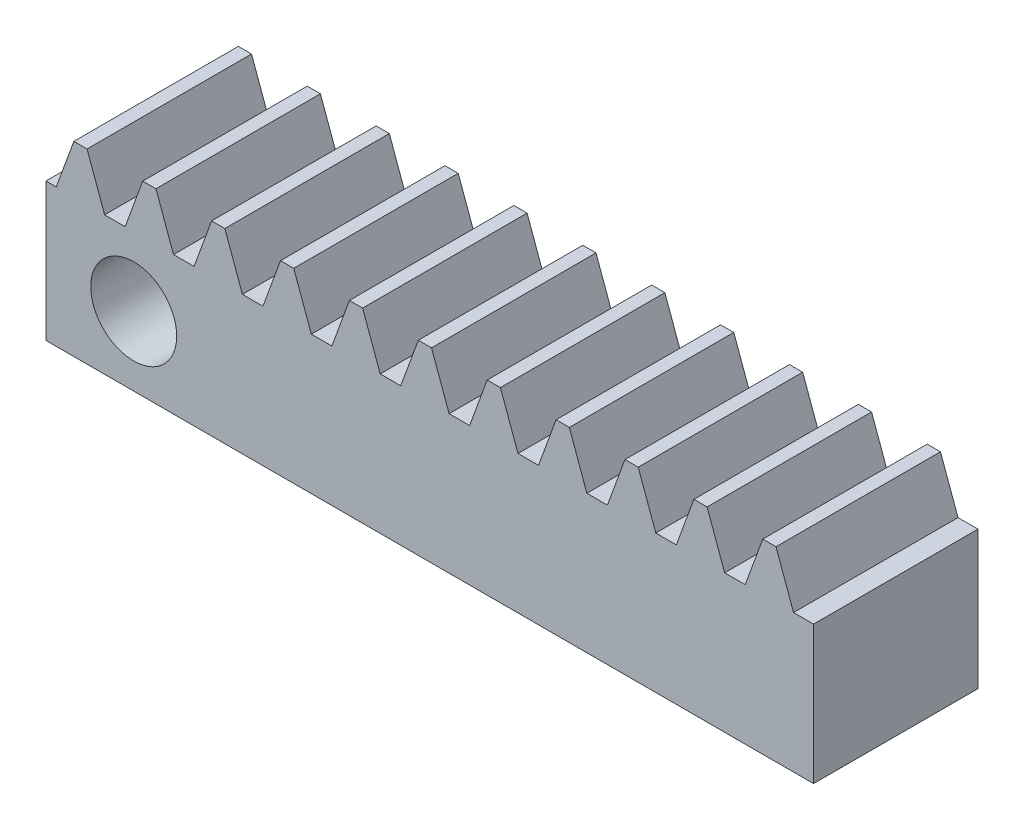
SolidWorks part; units mm, degrees
material "Plain Carbon Steel"
ref_plane "Plane1" through (0, 0, 0) normal (0, 0, 1) x (1, 0, 0)
ref_plane "Plane2" through (0, 0, 0) normal (0, 1, 0) x (1, 0, 0)
ref_plane "Plane3" through (0, 0, 0) normal (1, 0, 0) x (0, 0, -1)
sketch "HoldingSke" plane through (0, 0, 0) normal (0, 1, 0) x (1, 0, 0)
  line L0 (0, 0) -> (389.1506, -326.5361)
  line L1 (-15, 0) -> (100, 0) construction
  line L2 (0, 0) -> (-2.1039, 2.3779)
  line L3 (0, 0) -> (-11.863, 4.5341)
  line L4 (0, 0) -> (8.3795, 2.0892)
  line L5 (0, 0) -> (-23.7986, -8.8762)
  line L6 (0, 0) -> (-10.5278, -7.1032)
  line L9 (-71.009, 38.7566) -> (-23.2726, 56.1312)
  line L10 (-76.2, 71.12) -> (-66.675, 71.12)
  line L11 (0, 0) -> (-9.525, 0)
  line L12 (-76.2, 101.6) -> (-76.1492, 101.6)
  line L13 (24.9733, 27.94) -> (52.9518, 28.4284)
  line L14 (24.9733, 27.94) -> (25.0241, 27.9398)
  line L15 (24.9733, 27.94) -> (100.4021, 29.52)
  circle A0 centre (0, 0) radius 19.05
  circle A1 centre (0, 0) radius 4.7625
  circle A2 centre (0, 0) radius 12.7
  dimension "MPH" = 9.525
  dimension "Diameter" = 38.1
  dimension "Num_teeth" = 14
  dimension "Pitch" = 508
  dimension "Width" = 9.525
  dimension "Show_teeth" = 400
  dimension "Thickness" = 12.7
  dimension "Ap" = 20
  dimension "Pitch_height" = 9.525
  dimension "Backlash" = 0.0508
  dimension "Addendum_fac" = 1
  dimension "Dedendum_fac" = 1.2
  dimension "Clearance_fac" = 0.2
  dimension "Dedendum_add" = 0.0508
  dimension "Length" = 50.8
sketch "BlankSke" plane through (0, 0, 0) normal (0, 0, 1) x (1, 0, 0)
  line L1 (0, 0) -> (44.45, 0)
  line L2 (0, 0) -> (0, 10.795)
  line L3 (0, 10.795) -> (44.45, 10.795)
  line L4 (44.45, 0) -> (44.45, 10.795)
  dimension "Length" = 44.45
  dimension "Blank_height" = 10.795
extrude "Blank" add sketch "BlankSke" against normal blind 9.525
sketch "TooCutSkeIll" plane through (0, 0, 0) normal (0, 0, 1) x (1, 0, 0)
  line L0 (-1.5999, 10.7616) -> (-0.6682, 8.2016)
  line L1 (-0.3817, 8.001) -> (0.3817, 8.001)
  line L2 (0.6682, 8.2016) -> (1.5999, 10.7616)
  line L3 (44.45, 10.795) -> (0, 10.795) construction
  line L4 (0, 0) -> (0, 64.897) construction
  line L5 (-13.208, 9.525) -> (12.954, 9.525) construction
  line L6 (0, 0) -> (44.45, 0) construction
  line L7 (1.1499, 9.525) -> (1.1499, 48.7463) construction
  line L8 (-1.1499, 9.525) -> (-1.1499, 48.7463) construction
  line L9 (1.6477, 10.795) -> (1.6477, 10.8204)
  line L10 (-1.6477, 10.795) -> (-1.6477, 10.8204)
  line L11 (-1.6477, 10.8204) -> (1.6477, 10.8204)
  arc A0 (0.3817, 8.001) -> (0.6682, 8.2016) centre (0.3817, 8.3058) ccw
  arc A1 (-0.6682, 8.2016) -> (-0.3817, 8.001) centre (-0.3817, 8.3058) ccw
  arc A2 (1.6477, 10.795) -> (1.5999, 10.7616) centre (1.6477, 10.7442) ccw
  arc A3 (-1.5999, 10.7616) -> (-1.6477, 10.795) centre (-1.6477, 10.7442) ccw
  dimension "Root_fillet" = 0.3048
  dimension "Break_rad" = 0.0508
  dimension "Pitch_height" = 9.525
  dimension "Gap_width" = 2.2997
  dimension "Dedendum" = 1.524
  dimension "Addendum_plus" = 1.2954
  dimension "Pressure_angle" = 20
extrude "ToothCutIll" [suppressed] cut sketch "TooCutSkeIll" against normal through all
sketch "TooCutSkeSim" plane through (0, 0, 0) normal (0, 0, 1) x (1, 0, 0)
  line L0 (0.5952, 8.001) -> (-0.5952, 8.001)
  line L1 (1.6213, 10.8204) -> (0.5952, 8.001)
  line L2 (0, 17.4625) -> (0, 53.467) construction
  line L3 (1.6213, 10.8204) -> (-1.6213, 10.8204)
  line L6 (-1.6213, 10.8204) -> (-0.5952, 8.001)
  line L9 (-1.1499, 9.525) -> (1.1499, 9.525) construction
  line L10 (0, 0) -> (44.45, 0) construction
  line L11 (1.1499, 9.525) -> (1.1499, 53.467) construction
  line L12 (-1.1499, 9.525) -> (-1.1499, 53.467) construction
  dimension "Pitch_height" = 9.525
  dimension "Pressure_angle" = 20
  dimension "Gap_width" = 2.2997
  dimension "Dedendum" = 1.524
  dimension "Addendum_plus" = 1.2954
extrude "ToothCutSim" cut sketch "TooCutSkeSim" against normal through all
pattern_linear "TeethCuts" count 12 spacing 3.9898 along (1, 0, 0) of "ToothCutIll", "ToothCutSim"
sketch "Sketch1" plane through (0, 0, 0) normal (0, 0, 1) x (1, 0, 0)
  line L0 (0, 8.001) -> (0, 0) construction
  line L2 (0, 4.0005) -> (44.45, 4.0005) construction
  line L3 (44.45, 0) -> (44.45, 8.001) construction
  circle A0 centre (5.08, 4.0005) radius 2.4892
  dimension "D3" = 4.9784
  dimension "D1" = 5.08
extrude "Cut-Extrude1" cut sketch "Sketch1" against normal blind 14.478
equation "' \"Pitch@HoldingSke\" = 4"
equation "' \"Num_teeth@HoldingSke\" = 12"
equation "' \"Ap@HoldingSke\" =  20"
equation "' \"Width@HoldingSke\" = 0.25"
equation "' \"Show_teeth@HoldingSke\" = 500"
equation "' \"Backlash@HoldingSke\" = 0.009"
equation "' \"Addendum_fac@HoldingSke\" = 1.0"
equation "' \"Dedendum_fac@HoldingSke\" = 1.25"
equation "' \"Dedendum_add@HoldingSke\" = 0.00005"
equation "' \"Clearance_fac@HoldingSke\" = 0.25"
equation "' \"Pitch_height@HoldingSke\" = 1"
equation "' \"Length@HoldingSke\" = 4.71"
equation "\"MPH@HoldingSke\" = \"Dedendum_fac@HoldingSke\" / \"Pitch@HoldingSke\" + 2 * \"Dedendum_add@HoldingSke\" + 0.002"
equation "\"MPH@HoldingSke\" = ((sgn( \"MPH@HoldingSke\" - \"Pitch_height@HoldingSke\")+1)*( \"MPH@HoldingSke\" - \"Pitch_height@HoldingSke\"))/2 + \"Pitch_height@HoldingSke\""
equation "\"Blank_height@BlankSke\" = \"Pitch_height@HoldingSke\" + \"Addendum_fac@HoldingSke\"  / \"Pitch@HoldingSke\" "
equation "\"Length@BlankSke\"=1.75"
equation "\"Face_width@Blank\" = \"Width@HoldingSke\""
equation "\"Pressure_angle@TooCutSkeIll\" = \"Ap@HoldingSke\""
equation "\"Addendum_plus@TooCutSkeIll\" =  \"Addendum_fac@HoldingSke\"  / \"Pitch@HoldingSke\" + 0.001"
equation "\"Dedendum@TooCutSkeIll\" = \"Dedendum_fac@HoldingSke\"  / \"Pitch@HoldingSke\""
equation "\"Pitch_height@TooCutSkeIll\" =  \"MPH@HoldingSke\""
equation "\"Gap_width@TooCutSkeIll\" = 3.14159265 / 2 / \"Pitch@HoldingSke\" + 6 * \"Backlash@HoldingSke\""
equation "\"Pressure_angle@TooCutSkeSim\" = \"Ap@HoldingSke\""
equation "\"Addendum_plus@TooCutSkeSim\" =  \"Addendum_fac@HoldingSke\"  / \"Pitch@HoldingSke\" + 0.001"
equation "\"Dedendum@TooCutSkeSim\" = \"Dedendum_fac@HoldingSke\"  / \"Pitch@HoldingSke\""
equation "\"Pitch_height@TooCutSkeSim\" =  \"MPH@HoldingSke\""
equation "\"Gap_width@TooCutSkeSim\" = 3.14159265 / 2 / \"Pitch@HoldingSke\" + 6 * \"Backlash@HoldingSke\""
equation "\"Root_fillet@TooCutSkeIll\" = \"Clearance_fac@HoldingSke\" / \"Pitch@HoldingSke\" + \"Dedendum_add@HoldingSke\""
equation "\"Break_rad@TooCutSkeIll\" = 0.02 / \"Pitch@HoldingSke\" * 2"
equation "\"Linear_pitch@TeethCuts\" = 3.14159265 / \"Pitch@HoldingSke\""
equation "\"Num_teeth@HoldingSke\" = int( ( \"Length@HoldingSke\" + 0 ) / (3.14159265 / \"Pitch@HoldingSke\")) + 0.9999  + 1"
equation " \"Num_teeth@TeethCuts\" = int( \"Show_teeth@HoldingSke\" ) + 1"
equation " \"Num_teeth@TeethCuts\" = ((sgn( \"Num_teeth@TeethCuts\" - \"Num_teeth@HoldingSke\" )-1)*( \"Num_teeth@TeethCuts\" - \"Num_teeth@HoldingSke\" ))/-2+ \"Num_teeth@HoldingSke\""
equation " \"Num_teeth@TeethCuts\" = ((sgn( \"Num_teeth@TeethCuts\" - 2.0)+1)*( \"Num_teeth@TeethCuts\" - 2.0))/2 +2.0"
